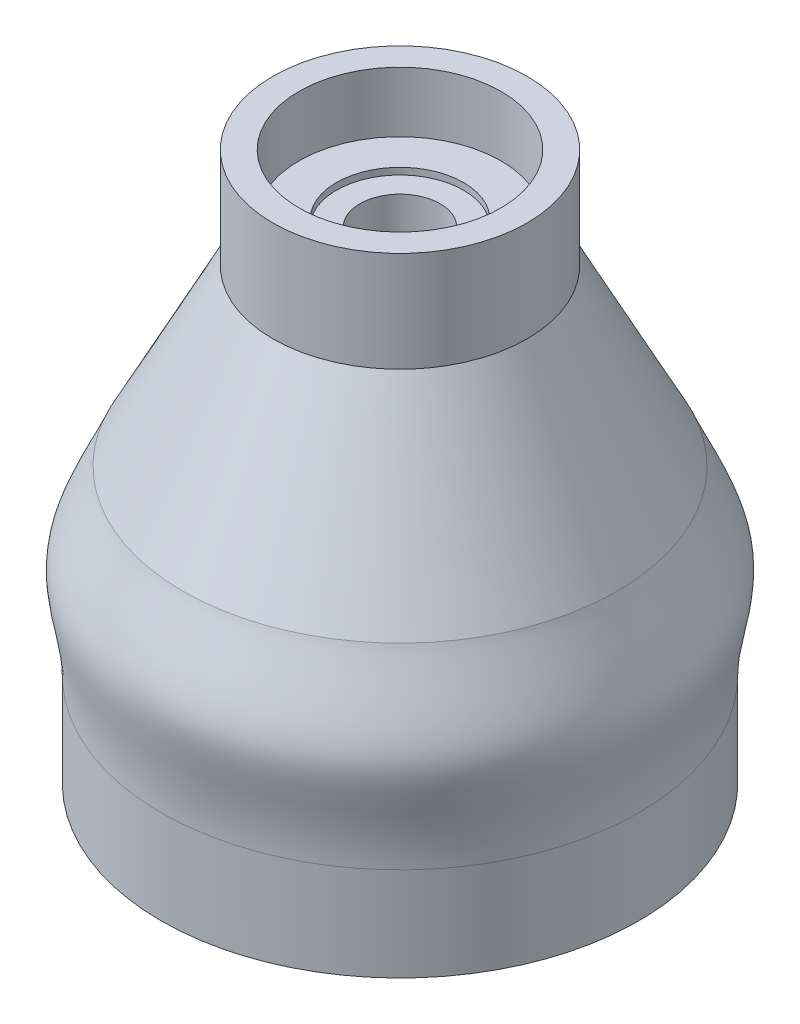
SolidWorks part; units mm, degrees
ref_plane "Front Plane" through (0, 0, 0) normal (0, 0, 1) x (1, 0, 0)
ref_plane "Top Plane" through (0, 0, 0) normal (0, 1, 0) x (1, 0, 0)
ref_plane "Right Plane" through (0, 0, 0) normal (1, 0, 0) x (0, 0, -1)
sketch "Sketch10" plane through (0, 0, 0) normal (1, 0, 0) x (0, 0, -1)
  line L0 (-6, 37) -> (-6, 73)
  line L1 (-19, 68) -> (-32.4524, 42.06)
  line L2 (-9.5, 36) -> (-9.5, 37)
  line L3 (-9.5, 37) -> (-6, 37)
  line L4 (-12.3, 36) -> (-12.3, 74) construction
  line L5 (-12.3, 55) -> (-3.9828, 55) construction
  line L6 (-9.5, 74) -> (-9.5, 73)
  line L7 (-9.5, 73) -> (-6, 73)
  line L12 (-31.2, 27) -> (-15.1, 27)
  line L22 (-15.1, 27) -> (-15.1, 36)
  line L23 (-9.5, 36) -> (-15.1, 36)
  line L53 (-19, 83) -> (-15.1, 83)
  line L55 (-19, 83) -> (-19, 68)
  line L57 (-15.1, 74) -> (-9.5, 74)
  line L58 (-15.1, 74) -> (-15.1, 83)
  line L64 (0, 0) -> (0, 94.4106) construction
  line L84 (-35.7, 0) -> (-31.2, 0)
  line L85 (-35.7, 15) -> (-35.7, 0)
  line L86 (-31.2, 27) -> (-31.2, 0)
  spline S0 degree 3 poles (-35.7, 15) (-35.7, 21.9985) (-38.1711, 26.6219) (-36.3582, 34.0611) (-33.1908, 40.0315) (-32.4524, 42.06) knots 0 0 0 0 0.519622 0.619622 1 1 1 1
  dimension "D1" = 32.4524
  dimension "D2" = 37.0702
  dimension "D3" = 31.052
  dimension "D4" = 19
  dimension "D5" = 15.1
  dimension "D6" = 19
  dimension "D7" = 31.2
  dimension "D8" = 35.7
  dimension "D9" = 15
  dimension "D10" = 27
  dimension "D11" = 36
  dimension "D12" = 42.06
  dimension "D13" = 68
  dimension "D14" = 74
  dimension "D15" = 3.5
  dimension "D16" = 1
revolve "Revolve1" add sketch "Sketch10" angle 360 about L64
chamfer "Chamfer3" distance 1 angle 60 2 edges at (0, 0, -35.7) (0, 0, -31.2)
